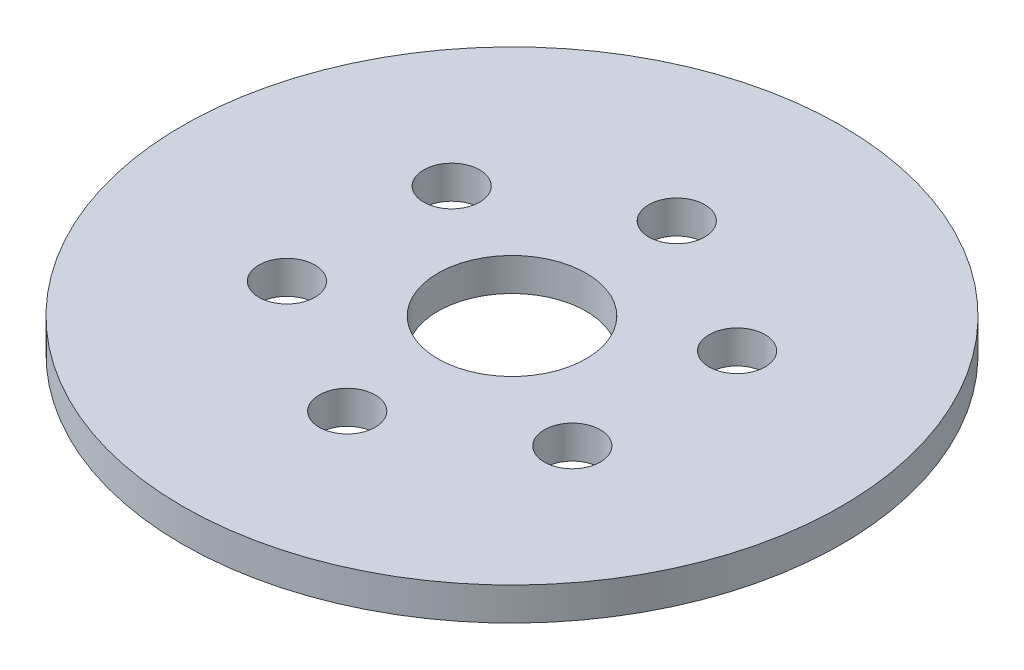
SolidWorks part; units mm, degrees
ref_plane "前视基准面" through (0, 0, 0) normal (0, 0, 1) x (1, 0, 0)
ref_plane "上视基准面" through (0, 0, 0) normal (0, 1, 0) x (1, 0, 0)
ref_plane "右视基准面" through (0, 0, 0) normal (1, 0, 0) x (0, 0, -1)
sketch "草图1" plane through (0, 0, 0) normal (0, 1, 0) x (1, 0, 0)
  circle A0 centre (0, 0) radius 20
  circle A1 centre (0, 0) radius 4.5
  dimension "D1" = 40
  dimension "D2" = 9
extrude "凸台-拉伸1" add sketch "草图1" along normal blind 2
sketch "草图2" plane through (0, 2, 0) normal (0, 1, 0) x (1, 0, 0)
  line L0 (0, -10) -> (0, 10) construction
  circle A0 centre (0, 0) radius 10 construction
  circle A1 centre (0, 10) radius 1.7
  circle A2 centre (0, 0) radius 10 construction
  circle A3 centre (8.6603, 5) radius 1.7
  circle A4 centre (0, 0) radius 10 construction
  circle A5 centre (8.6603, -5) radius 1.7
  circle A6 centre (0, 0) radius 10 construction
  circle A7 centre (0, -10) radius 1.7
  circle A8 centre (0, 0) radius 10 construction
  circle A9 centre (-8.6603, -5) radius 1.7
  circle A10 centre (0, 0) radius 10 construction
  circle A11 centre (-8.6603, 5) radius 1.7
  point P23 (0, 0)
  dimension "D1" = 20
  dimension "D2" = 3.4
  dimension "D3" = 6
extrude "切除-拉伸1" cut sketch "草图2" against normal through all
